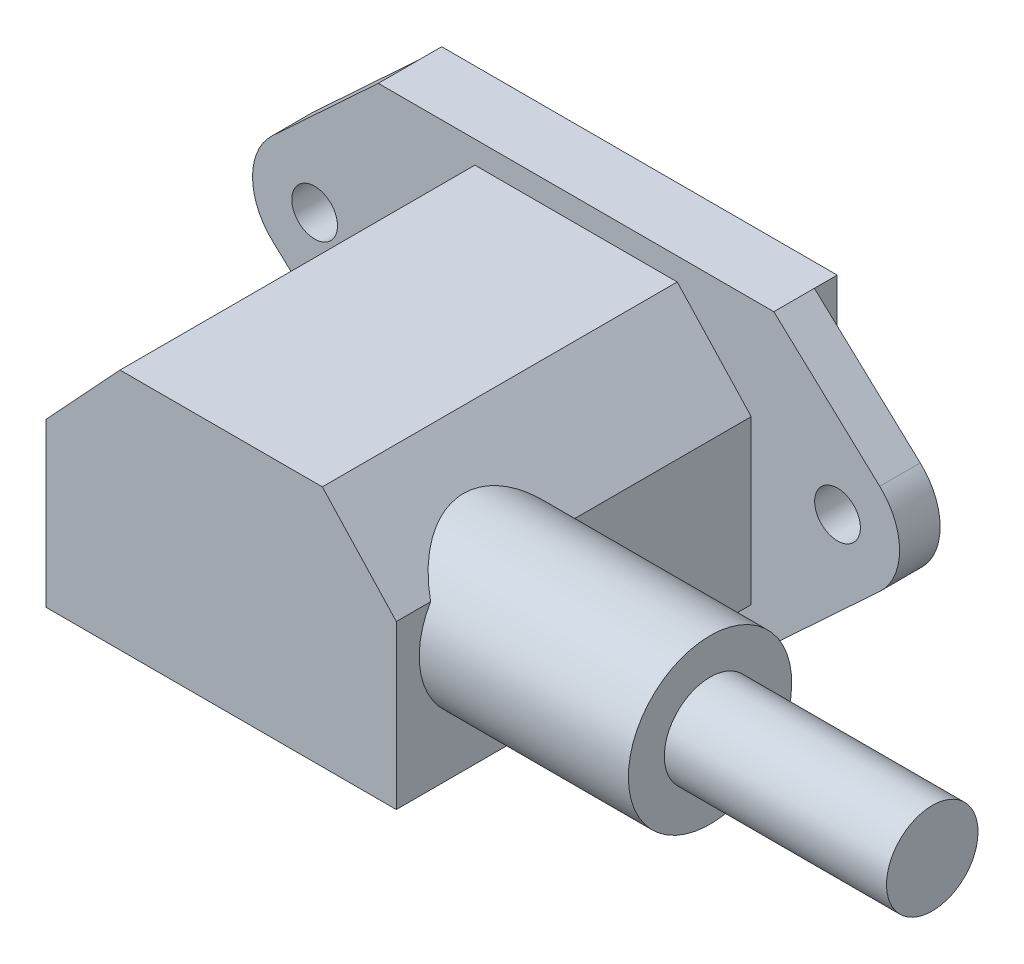
SolidWorks part; units mm, degrees
ref_plane "前视基准面" through (0, 0, 0) normal (0, 0, 1) x (1, 0, 0)
ref_plane "上视基准面" through (0, 0, 0) normal (0, 1, 0) x (1, 0, 0)
ref_plane "右视基准面" through (0, 0, 0) normal (1, 0, 0) x (0, 0, -1)
sketch "草图1" plane through (0, 0, 0) normal (0, 0, 1) x (1, 0, 0)
  line L0 (0, 0) -> (0, 16.3) construction
  line L1 (7.25, 16.3) -> (-7.25, 16.3)
  line L2 (-7.25, 16.3) -> (-12.175, 11)
  line L3 (-12.175, 11) -> (-12.175, 0)
  line L4 (-12.175, 0) -> (12.175, 0)
  line L5 (12.175, 11) -> (12.175, 0)
  line L6 (7.25, 16.3) -> (12.175, 11)
  line L8 (-15.13, -2.85) -> (15.13, -2.85)
  line L9 (-15.13, -2.85) -> (-15.13, 19.15)
  line L10 (-15.13, 19.15) -> (15.13, 19.15)
  line L11 (15.13, -2.85) -> (15.13, 19.15)
  line L12 (-15.13, -2.85) -> (15.13, 19.15) construction
  line L13 (-15.13, 19.15) -> (15.13, -2.85) construction
  point P9 (0, 8.15)
  dimension "D1" = 14.5
  dimension "D2" = 24.35
  dimension "D3" = 16.3
  dimension "D4" = 11
  dimension "D5" = 2.85
  dimension "D6" = 22
  dimension "D7" = 30.26
extrude "凸台-拉伸1" add sketch "草图1" along normal blind 1.75
sketch "草图2" plane through (0, 0, 1.75) normal (0, 0, 1) x (1, 0, 0)
  line L0 (-15.13, 19.15) -> (15.13, 19.15)
  line L1 (15.13, 19.15) -> (23.2312, 11.6317)
  line L2 (23.2312, 4.6683) -> (15.13, -2.85)
  line L3 (15.13, -2.85) -> (-15.13, -2.85)
  line L4 (0, 0) -> (0, 19.15) construction
  line L5 (-12.175, 0) -> (12.175, 0) construction
  line L6 (-23.2312, 4.6683) -> (-15.13, -2.85)
  line L7 (-15.13, 19.15) -> (-23.2312, 11.6317)
  line L8 (20, 8.15) -> (15.13, 8.15) construction
  line L9 (15.13, -2.85) -> (15.13, 19.15) construction
  arc A0 (23.2312, 11.6317) -> (23.2312, 4.6683) centre (20, 8.15) cw
  arc A1 (-23.2312, 11.6317) -> (-23.2312, 4.6683) centre (-20, 8.15) ccw
  circle A2 centre (-20, 8.15) radius 1.75
  circle A3 centre (20, 8.15) radius 1.75
  point P20 (-24.75, 8.15)
  point P24 (24.75, 8.15)
  dimension "D2" = 3.5
  dimension "D1" = 49.5
  dimension "D3" = 40
extrude "凸台-拉伸2" add sketch "草图2" along normal blind 3.1
sketch "草图3" plane through (0, 0, 4.85) normal (0, 0, 1) x (1, 0, 0)
  line L0 (13.4, -1.125) -> (-13.4, -1.125)
  line L1 (-13.4, -1.125) -> (-13.4, 11.3328)
  line L2 (-13.4, 11.3328) -> (-7.7389, 17.425)
  line L3 (-7.7389, 17.425) -> (7.7389, 17.425)
  line L4 (0, 17.425) -> (0, -1.125) construction
  line L6 (-7.25, 16.3) -> (-12.175, 11) construction
  line L7 (-7.25, 16.3) -> (-7.25, 17.425) construction
  line L8 (-10.5694, 14.3789) -> (-9.7125, 13.65) construction
  line L9 (13.4, -1.125) -> (13.4, 11.3328)
  line L10 (13.4, 11.3328) -> (7.7389, 17.425)
  point P3 (0, 8.15)
  dimension "D1" = 18.55
  dimension "D2" = 26.8
extrude "凸台-拉伸3" add sketch "草图3" along normal offset from surface (27.15 mm away) 32 up to face at (0, 8.15, 0)
sketch "草图4" plane through (13.4, 0, 0) normal (1, 0, 0) x (0, 0, -1)
  line L0 (-32, 11.3328) -> (-32, -1.125) construction
  line L1 (-4.85, 9.9) -> (-4.85, 6.4) construction
  line L2 (-4.85, 9.9) -> (-4.85, 6.4) construction
  line L3 (-4.85, 8.15) -> (-24, 8.15) construction
  circle A0 centre (-24, 8.15) radius 6.25
  dimension "D1" = 12.5
  dimension "D2" = 8
extrude "凸台-拉伸4" add sketch "草图4" along normal blind 16 and the other way up to next
sketch "草图5" plane through (29.4, 0, 0) normal (1, 0, 0) x (0, 0, -1)
  circle A0 centre (-24, 8.15) radius 3.5
  dimension "D1" = 7
extrude "凸台-拉伸5" add sketch "草图5" along normal blind 17
sketch "草图6" plane through (0, 0, 1.75) normal (0, 0, -1) x (-1, 0, 0)
  line L6 (-12.175, 11) -> (-12.175, 0)
  line L7 (-12.175, 0) -> (12.175, 0)
  line L8 (12.175, 0) -> (12.175, 11)
  line L9 (12.175, 11) -> (7.25, 16.3)
  line L10 (7.25, 16.3) -> (-7.25, 16.3)
  line L11 (-7.25, 16.3) -> (-12.175, 11)
  line L12 (-12.175, 11) -> (-12.175, 0)
  line L13 (-12.175, 0) -> (12.175, 0)
  line L14 (12.175, 0) -> (12.175, 11)
  line L15 (12.175, 11) -> (7.25, 16.3)
  line L16 (7.25, 16.3) -> (-7.25, 16.3)
  line L17 (-7.25, 16.3) -> (-12.175, 11)
  dimension "D1" = 0
extrude "切除-拉伸1" cut sketch "草图6" against normal blind 17
